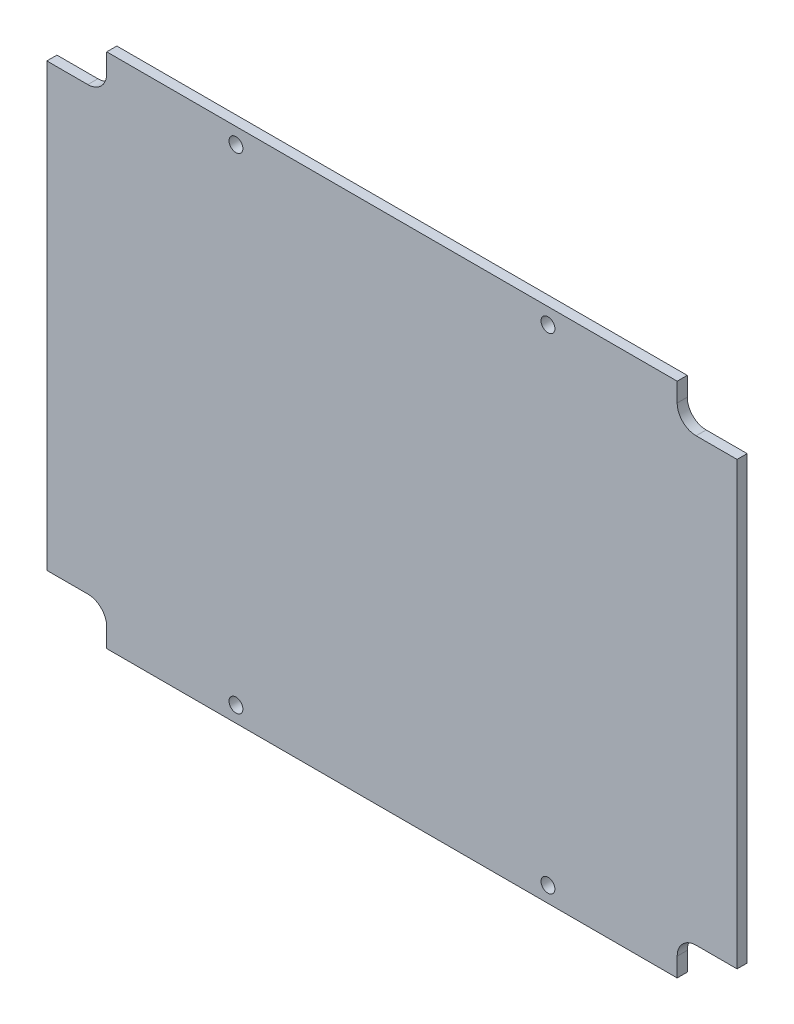
SolidWorks part; units mm, degrees
ref_plane "Front Plane" through (0, 0, 0) normal (0, 0, 1) x (1, 0, 0)
ref_plane "Top Plane" through (0, 0, 0) normal (0, 1, 0) x (1, 0, 0)
ref_plane "Right Plane" through (0, 0, 0) normal (1, 0, 0) x (0, 0, -1)
sketch "Sketch1" plane through (0, 0, 0) normal (0, 0, 1) x (1, 0, 0)
  line L0 (54.0064, 79.9519) -> (44.5064, 79.9519)
  line L1 (-45.9936, 85.9519) -> (44.5064, 85.9519)
  line L2 (54.0064, 79.9519) -> (54.0064, 9.9519)
  line L3 (44.5064, 79.9519) -> (44.5064, 85.9519)
  line L4 (-55.4936, 79.9519) -> (-55.4936, 9.9519)
  line L5 (-45.9936, 3.9519) -> (44.5064, 3.9519)
  line L6 (54.0064, 9.9519) -> (44.5064, 9.9519)
  line L7 (44.5064, 9.9519) -> (44.5064, 3.9519)
  line L8 (-45.9936, 3.9519) -> (-45.9936, 9.9519)
  line L9 (-45.9936, 9.9519) -> (-55.4936, 9.9519)
  line L10 (-45.9936, 85.9519) -> (-45.9936, 79.9519)
  line L11 (-45.9936, 79.9519) -> (-55.4936, 79.9519)
  circle A0 centre (-25.4936, 83.4519) radius 1.1
  circle A1 centre (24.0064, 83.4519) radius 1.1
  circle A2 centre (24.0064, 6.4519) radius 1.1
  circle A3 centre (-25.4936, 6.4519) radius 1.1
  dimension "D1" = 2.2
  dimension "D2" = 2.5
  dimension "D3" = 82
  dimension "D4" = 109.5
  dimension "D5" = 2.5
  dimension "D6" = 9.5
  dimension "D7" = 2.5
  dimension "D8" = 2.5
  dimension "D9" = 30
  dimension "D10" = 30
  dimension "D11" = 30
  dimension "D12" = 30
  dimension "D13" = 6
extrude "Boss-Extrude1" add sketch "Sketch1" along normal blind 1.6
fillet "Fillet1" radius 3 4 edges at (44.5064, 9.9519, 0.8) (-45.9936, 9.9519, 0.8) (-45.9936, 79.9519, 0.8) (44.5064, 79.9519, 0.8)
